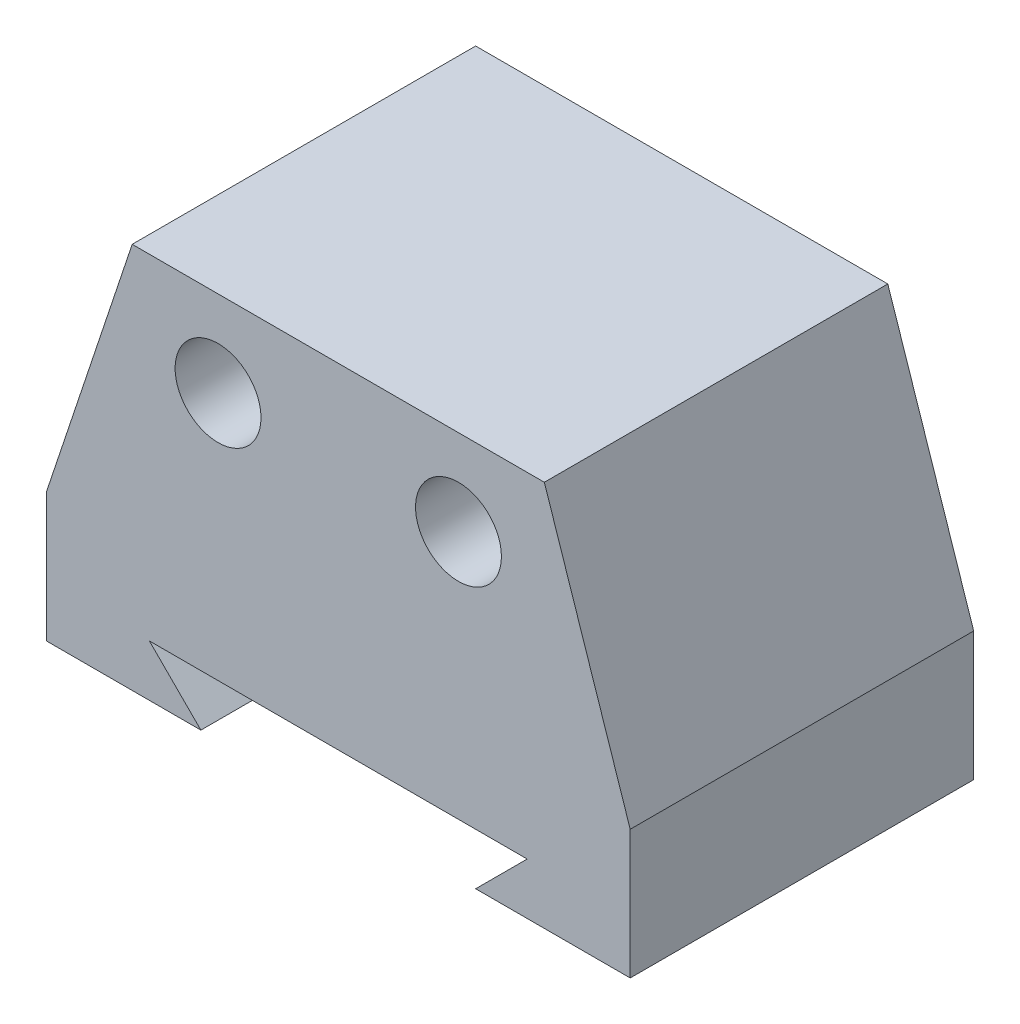
SolidWorks part; units mm, degrees
ref_plane "Front Plane" through (0, 0, 0) normal (0, 0, 1) x (1, 0, 0)
ref_plane "Top Plane" through (0, 0, 0) normal (0, 1, 0) x (1, 0, 0)
ref_plane "Right Plane" through (0, 0, 0) normal (1, 0, 0) x (0, 0, -1)
sketch "Sketch1" plane through (0, 0, 0) normal (0, 0, 1) x (1, 0, 0)
  line L0 (0, 0) -> (31381.9831, 0) construction
  line L1 (0, 0) -> (0, 31381.9831) construction
  line L2 (-22, 6) -> (22, 6)
  line L3 (22, 6) -> (16, 0)
  line L4 (16, 0) -> (34, 0)
  line L5 (34, 0) -> (34, 15)
  line L6 (34, 15) -> (24, 45)
  line L8 (24, 45) -> (-24, 45)
  line L10 (-34, 15) -> (-24, 45)
  line L11 (-34, 0) -> (-34, 15)
  line L12 (-16, 0) -> (-34, 0)
  line L13 (-22, 6) -> (-16, 0)
  circle A0 centre (-14, 35) radius 5
  circle A1 centre (14, 35) radius 5
  point P14 (0, 45)
  point P19 (0, 6)
  point P21 (0, 0)
  point P22 (0, 0)
  dimension "D7" = 10
  dimension "D1" = 68
  dimension "D2" = 18
  dimension "D3" = 15
  dimension "D4" = 45
  dimension "D5" = 48
  dimension "D6" = 6
  dimension "D8" = 35
  dimension "D9" = 20
  dimension "D10" = 45
extrude "Boss-Extrude1" add sketch "Sketch1" along normal blind 40
